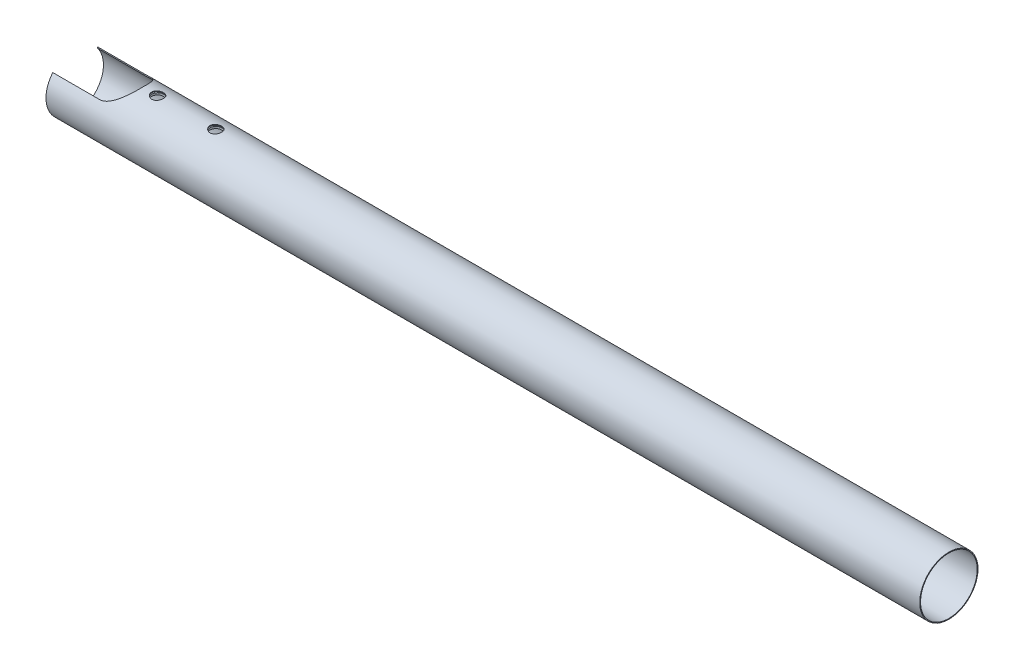
SolidWorks part; units mm, degrees
material "AISI 1035 Acier (SS)"
ref_plane "Plan1" through (0, 0, 0) normal (0, 0, 1) x (1, 0, 0)
ref_plane "Plan2" through (0, 0, 0) normal (0, 1, 0) x (1, 0, 0)
ref_plane "Plan3" through (0, 0, 0) normal (1, 0, 0) x (0, 0, -1)
ref_plane "Plan4" through (0, 26, 0) normal (0, 1, 0) x (-1, 0, 0)
sketch "Esquisse1" plane through (0, 0, 0) normal (1, 0, 0) x (0, 0, -1)
  circle A0 centre (0, 0) radius 30
  dimension "D1" = 60
extrude "Base-Extrusion" add sketch "Esquisse1" along normal blind 900
shell "Coque1" thickness 0.8
sketch "Esquisse2" plane through (0, 0, 0) normal (0, 1, 0) x (1, 0, 0)
  line L1 (-10, 23) -> (48, 23)
  line L2 (-10, 23) -> (-10, -23)
  line L3 (-10, -23) -> (48, -23)
  line L4 (70, 1) -> (70, -1)
  arc A0 (70, 1) -> (48, 23) centre (48, 1) ccw
  arc A1 (48, -23) -> (70, -1) centre (48, -1) ccw
  dimension "D1" = 22
extrude "Enlèv. mat.-Extru.1" cut sketch "Esquisse2" along normal blind 100
sketch "Esquisse4" plane through (0, 26, 0) normal (0, 1, 0) x (-1, 0, 0)
  line L1 (-160, 10) -> (-71, 10)
  line L2 (-160, 10) -> (-160, -10)
  line L3 (-160, -10) -> (-71, -10)
  line L4 (-71, 10) -> (-71, -10)
extrude "Boss.-Extru.1" add sketch "Esquisse4" along normal blind 2
sketch "Esquisse3" plane through (0, 0, 0) normal (0, 1, 0) x (1, 0, 0)
  circle A0 centre (85, 0) radius 6
  circle A1 centre (145, 0) radius 6
extrude "Enlèv. mat.-Extru.2" cut sketch "Esquisse3" along normal blind 100
